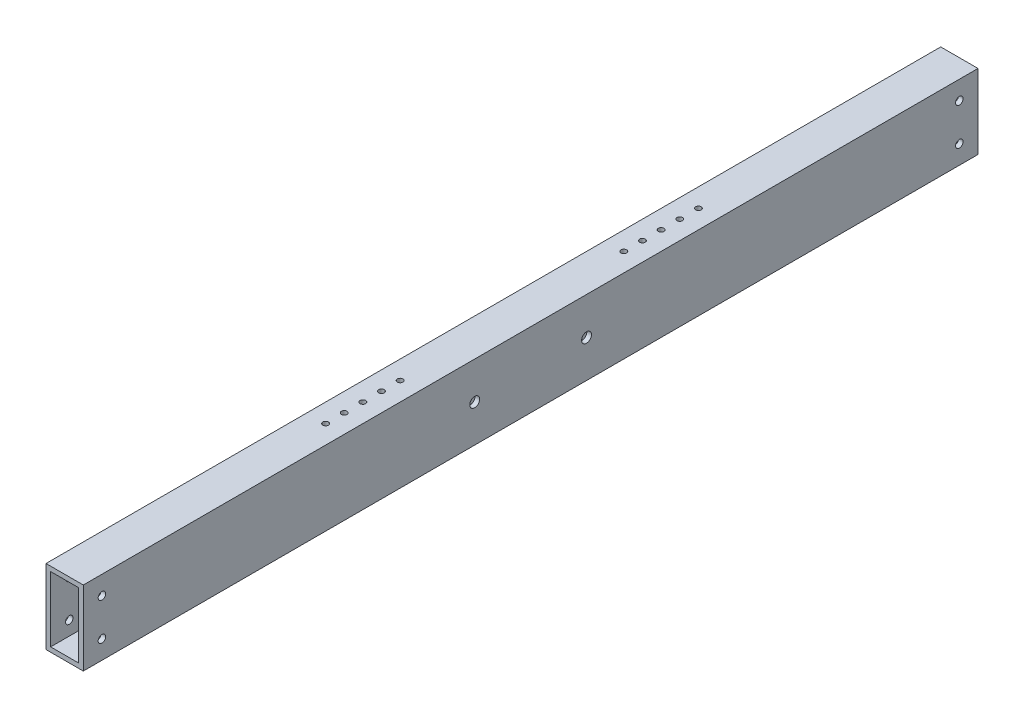
SolidWorks part; units mm, degrees
material "6061-T6 (SS)"
ref_plane "Front Plane" through (0, 0, 0) normal (0, 0, 1) x (1, 0, 0)
ref_plane "Top Plane" through (0, 0, 0) normal (0, 1, 0) x (1, 0, 0)
ref_plane "Right Plane" through (0, 0, 0) normal (1, 0, 0) x (0, 0, -1)
sketch "Sketch1" plane through (0, 0, 0) normal (0, 0, 1) x (1, 0, 0)
  line L0 (-9.525, 22.225) -> (9.525, 22.225)
  line L1 (-12.7, 25.4) -> (12.7, 25.4)
  line L2 (-12.7, 25.4) -> (-12.7, -25.4)
  line L3 (-12.7, -25.4) -> (12.7, -25.4)
  line L4 (12.7, 25.4) -> (12.7, -25.4)
  line L5 (-12.7, 25.4) -> (12.7, -25.4) construction
  line L6 (-12.7, -25.4) -> (12.7, 25.4) construction
  line L7 (9.525, 22.225) -> (9.525, -22.225)
  line L8 (-9.525, -22.225) -> (9.525, -22.225)
  line L9 (-9.525, 22.225) -> (-9.525, -22.225)
  point P0 (0, 0)
  dimension "D1" = 50.8
  dimension "D2" = 25.4
  dimension "D3" = 3.175
extrude "Boss-Extrude1" add sketch "Sketch1" along normal mid plane 609.6
hole_wizard "#10 Clearance Hole1" positions "Sketch4" profile "Sketch3" hole size "#10" standard "ANSI Inch" end condition through all
sketch "Sketch4" plane through (12.7, 0, 0) normal (1, 0, 0) x (0, 0, -1)
  line L0 (-304.8, 25.4) -> (304.8, 25.4) construction
  point P0 (-292.1, 12.7)
  point P13 (-292.1, -12.7)
  dimension "D2" = 12.7
  dimension "D1" = 2
sketch "Sketch3" plane through (12.7, 12.7, 292.1) normal (0, 1, 0) x (0, 0, -1)
  line L0 (0, 0) -> (0, 25.4)
  line L1 (0, 25.4) -> (2.5527, 25.4)
  line L2 (2.5527, 25.4) -> (2.5527, 0)
  line L5 (2.5527, 0) -> (0, 0)
  line L11 (0, -6.35) -> (0, 107.95) construction
  dimension "Thru Hole Dia." = 5.1054
  dimension "Thru Hole Depth" = 25.4
mirror "Mirror1" about plane through (0, 0, 0) normal (0, 0, 1) of "#10 Clearance Hole1"
hole_wizard "1/4 Clearance Hole2" positions "Sketch6" profile "Sketch5" hole size "1/4" standard "ANSI Inch" end condition through all
sketch "Sketch6" plane through (12.7, 0, 0) normal (1, 0, 0) x (0, 0, -1)
  line L0 (-38.1, 0) -> (38.1, 0) construction
  point P0 (-38.1, 0)
  point P2 (38.1, 0)
  dimension "D1" = 76.2
sketch "Sketch5" plane through (12.7, 0, 38.1) normal (0, 1, 0) x (0, 0, -1)
  line L0 (0, 0) -> (0, 25.4)
  line L1 (0, 25.4) -> (3.3782, 25.4)
  line L2 (3.3782, 25.4) -> (3.3782, 0)
  line L5 (3.3782, 0) -> (0, 0)
  line L11 (0, -6.35) -> (0, 107.95) construction
  dimension "Thru Hole Dia." = 6.7564
  dimension "Thru Hole Depth" = 25.4
sketch "Sketch7" plane through (0, 25.4, 0) normal (0, 1, 0) x (1, 0, 0)
  line L0 (-12.7, -304.8) -> (-12.7, 304.8) construction
  line L1 (12.7, 304.8) -> (-12.7, 304.8) construction
  circle A0 centre (0, 127) radius 1.905
  circle A1 centre (0, 114.3) radius 1.905
  circle A2 centre (0, 101.6) radius 1.905
  circle A3 centre (0, 88.9) radius 1.905
  circle A4 centre (0, 76.2) radius 1.905
  dimension "D1" = 3.81
  dimension "D2" = 12.7
  dimension "D3" = 177.8
  dimension "D4" = 5
extrude "Cut-Extrude1" cut sketch "Sketch7" against normal through all
mirror "Mirror2" about plane through (0, 0, 0) normal (0, 0, 1) of "Cut-Extrude1"
